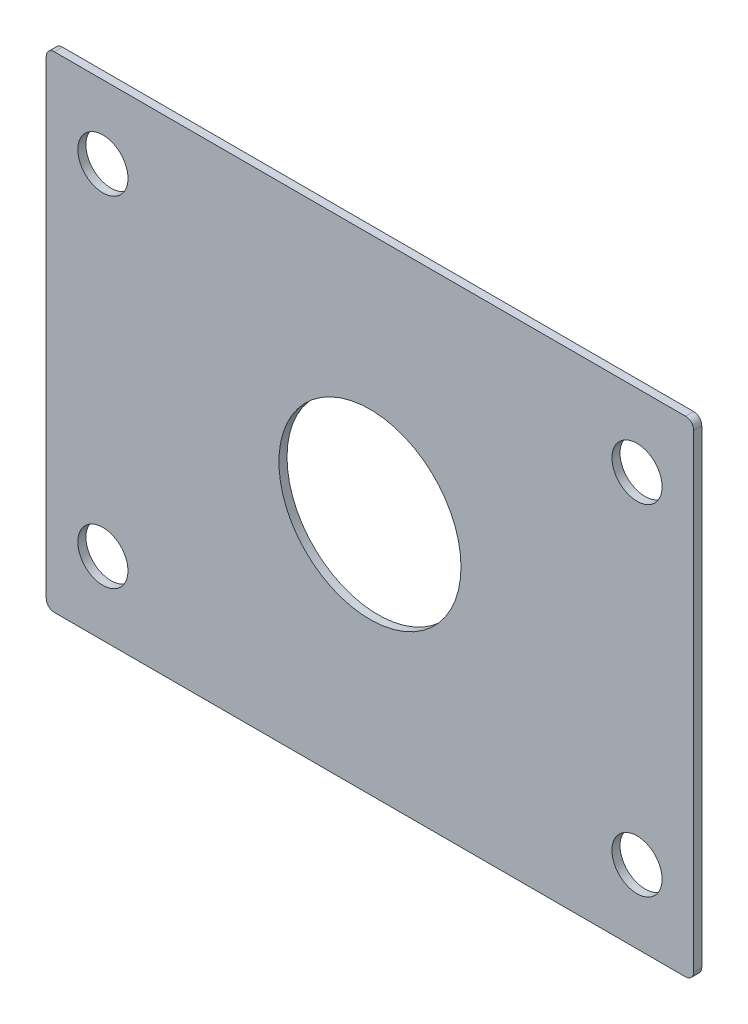
SolidWorks part; units mm, degrees
ref_plane "Front Plane" through (0, 0, 0) normal (0, 0, 1) x (1, 0, 0)
ref_plane "Top Plane" through (0, 0, 0) normal (0, 1, 0) x (1, 0, 0)
ref_plane "Right Plane" through (0, 0, 0) normal (1, 0, 0) x (0, 0, -1)
sketch "Sketch1" plane through (0, 0, 0) normal (0, 0, 1) x (1, 0, 0)
  line L1 (40, 30) -> (-40, 30)
  line L2 (40, 30) -> (40, -30)
  line L3 (40, -30) -> (-40, -30)
  line L4 (-40, 30) -> (-40, -30)
  line L5 (40, 30) -> (-40, -30) construction
  line L6 (40, -30) -> (-40, 30) construction
  point P0 (0, 0)
  point P5 (256.8098, -2.7083)
  point P6 (0, 0)
  dimension "D2" = 80
  dimension "D3" = 60
extrude "Boss-Extrude1" add sketch "Sketch1" along normal blind 1
sketch "Sketch2" plane through (0, 0, 1) normal (0, 0, 1) x (1, 0, 0)
  line L0 (40, 0) -> (-40, 0) construction
  line L1 (40, -30) -> (40, 30) construction
  line L2 (-40, 30) -> (-40, -30) construction
  line L3 (0, 30) -> (0, -30) construction
  line L4 (40, 30) -> (-40, 30) construction
  line L5 (-40, -30) -> (40, -30) construction
  line L7 (-33, -21) -> (33, -21) construction
  line L8 (-33, -21) -> (-33, 21) construction
  line L9 (-33, 21) -> (33, 21) construction
  line L10 (33, -21) -> (33, 21) construction
  line L11 (-33, -21) -> (33, 21) construction
  line L12 (-33, 21) -> (33, -21) construction
  circle A0 centre (-33, 21) radius 3.1
  circle A1 centre (33, 21) radius 3.1
  circle A2 centre (33, -21) radius 3.1
  circle A3 centre (-33, -21) radius 3.1
  circle A4 centre (0, 0) radius 11.25
  point P12 (0, 0)
  point P13 (0, 0)
  dimension "D3" = 6.2
  dimension "D4" = 22.5
  dimension "D1" = 66
  dimension "D2" = 42
extrude "Cut-Extrude1" cut sketch "Sketch2" against normal blind 10
fillet "Fillet1" radius 1 4 edges at (-40, -30, 0.5) (40, -30, 0.5) (40, 30, 0.5) (-40, 30, 0.5)
